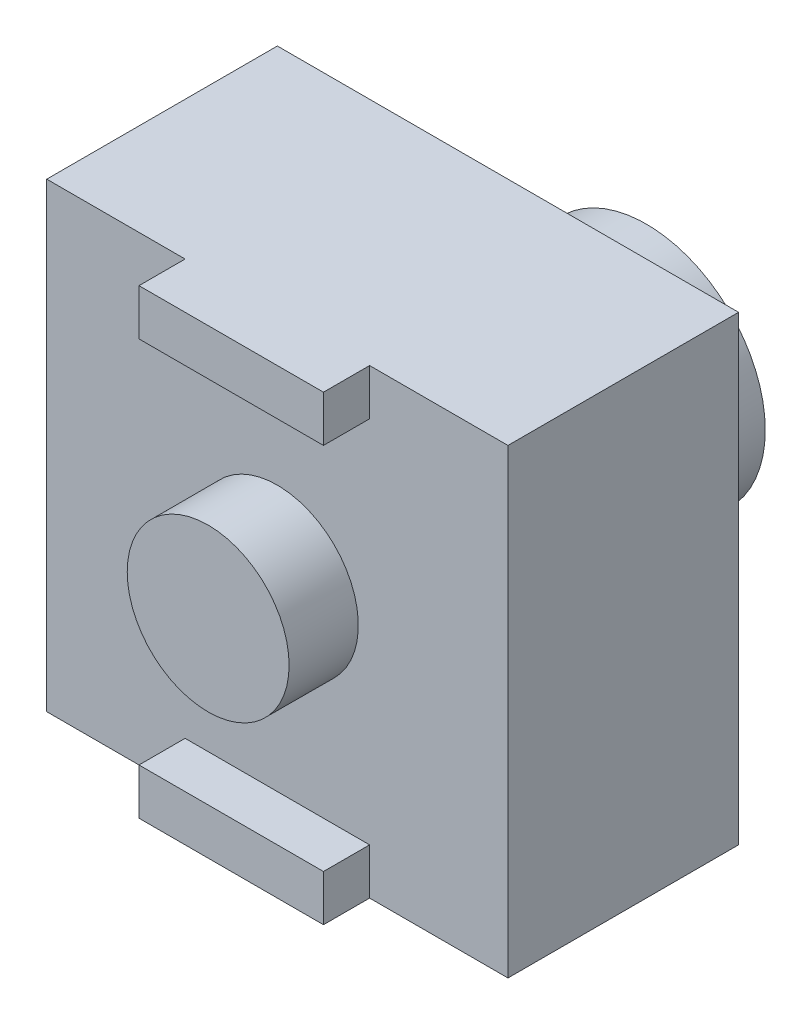
SolidWorks part; units mm, degrees
ref_plane "Front Plane" through (0, 0, 0) normal (0, 0, 1) x (1, 0, 0)
ref_plane "Top Plane" through (0, 0, 0) normal (0, 1, 0) x (1, 0, 0)
ref_plane "Right Plane" through (0, 0, 0) normal (1, 0, 0) x (0, 0, -1)
sketch "Sketch1" plane through (0, 0, 0) normal (0, 0, 1) x (1, 0, 0)
  line L1 (0, 0) -> (10, 0)
  line L2 (0, 0) -> (0, 10)
  line L3 (0, 10) -> (10, 10)
  line L4 (10, 0) -> (10, 10)
  dimension "D1" = 10
  dimension "D2" = 10
extrude "Boss-Extrude1" add sketch "Sketch1" along normal blind 5
sketch "Sketch2" plane through (0, 0, 0) normal (0, 0, -1) x (-1, 0, 0)
  line L0 (-10, 0) -> (-10, 10) construction
  line L1 (-10, 10) -> (0, 10) construction
  circle A0 centre (-5, 5) radius 2.5
  dimension "D1" = 5
  dimension "D2" = 5
extrude "Cut-Extrude1" cut sketch "Sketch2" against normal blind 4
sketch "Sketch3" plane through (0, 0, 4) normal (0, 0, -1) x (-1, 0, 0)
  line L0 (-10, 10) -> (0, 10) construction
  line L1 (0, 10) -> (0, 0) construction
  circle A0 centre (-5, 5) radius 1.755
  point P2 (0, 0)
  dimension "D1" = 5
  dimension "D2" = 5
extrude "Cut-Extrude2" cut sketch "Sketch3" against normal blind 1
sketch "Sketch4" plane through (0, 0, 4) normal (0, 0, -1) x (-1, 0, 0)
  circle A0 centre (-5, 5.0785) radius 2.5785
extrude "Boss-Extrude2" add sketch "Sketch4" along normal blind 7
sketch "Sketch5" plane through (0, 0, 4) normal (0, 0, 1) x (1, 0, 0)
  line L0 (0, 10) -> (0, 0) construction
  line L1 (0, 0) -> (10, 0) construction
  circle A0 centre (5, 5) radius 1.755
  dimension "D1" = 3.51
  dimension "D2" = 5
  dimension "D3" = 5
extrude "Boss-Extrude3" add sketch "Sketch5" along normal blind 2.5
ref_plane "Plane1" through (0, 5, 0) normal (0, -1, 0) x (-1, 0, 0)
sketch "Sketch6" plane through (0, 0, 5) normal (0, 0, 1) x (1, 0, 0)
  line L0 (10, 10) -> (0, 10) construction
  line L1 (3, 10) -> (7, 10)
  line L2 (3, 10) -> (3, 9)
  line L3 (3, 9) -> (7, 9)
  line L4 (7, 10) -> (7, 9)
  line L5 (10, 0) -> (10, 10) construction
  dimension "D1" = 1
  dimension "D2" = 4
  dimension "D3" = 3
extrude "Boss-Extrude4" add sketch "Sketch6" along normal blind 1
mirror "Mirror1" about plane through (0, 5, 0) normal (0, -1, 0) of "Boss-Extrude4"
